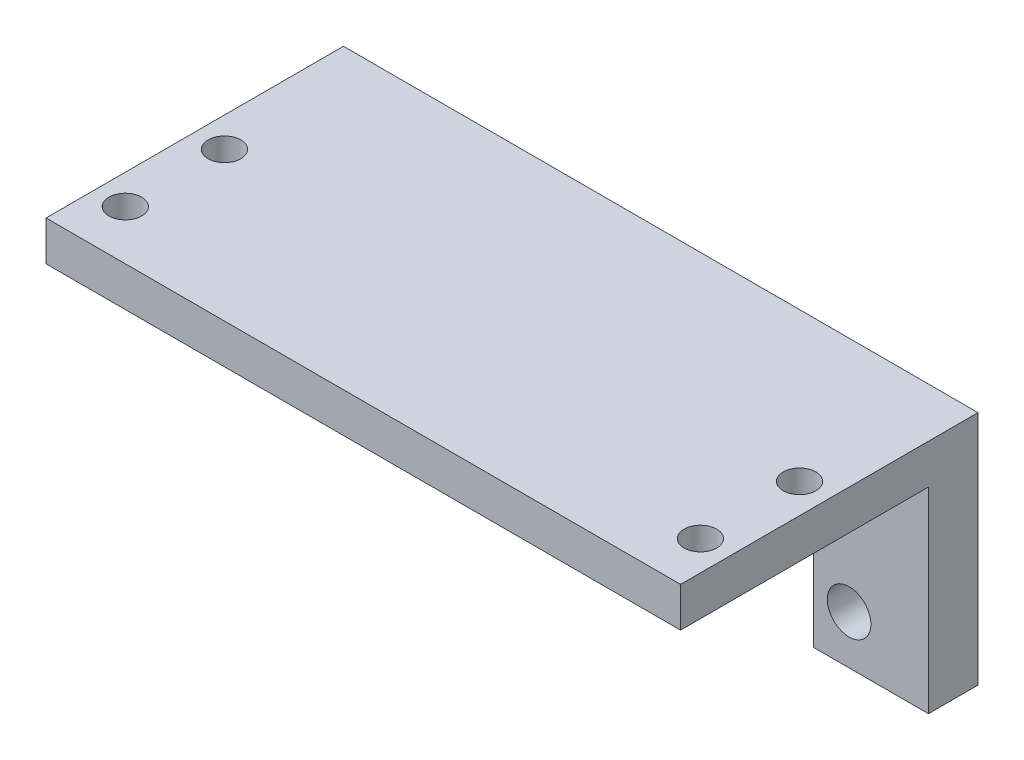
SolidWorks part; units mm, degrees
ref_plane "前视基准面" through (0, 0, 0) normal (0, 0, 1) x (1, 0, 0)
ref_plane "上视基准面" through (0, 0, 0) normal (0, 1, 0) x (1, 0, 0)
ref_plane "右视基准面" through (0, 0, 0) normal (1, 0, 0) x (0, 0, -1)
sketch "草图1" plane through (0, 0, 0) normal (0, 0, 1) x (1, 0, 0)
  line L0 (20.4, 0) -> (32, 0)
  line L1 (32, 0) -> (32, -19.8)
  line L2 (32, -19.8) -> (20.4, -19.8)
  line L3 (20.4, -19.8) -> (20.4, 0)
  line L4 (20.4, -9.9) -> (24.2798, -9.9) construction
  line L7 (0, 0) -> (0, -5.9432) construction
  line L12 (-32, -19.8) -> (-20.4, -19.8)
  line L13 (-32, 0) -> (-32, -19.8)
  line L14 (-20.4, 0) -> (-32, 0)
  line L15 (-20.4, -19.8) -> (-20.4, 0)
  circle A6 centre (24, -4.9) radius 2.2
  circle A7 centre (24, -14.9) radius 2.2
  circle A16 centre (-24, -14.9) radius 2.2
  circle A17 centre (-24, -4.9) radius 2.2
  point P4 (24, -4.9)
  point P14 (24, -14.9)
  point P21 (24, -4.9)
  point P22 (24, -14.9)
  dimension "D1" = 11.6
  dimension "D2" = 19.8
extrude "凸台-拉伸1" add sketch "草图1" along normal blind 5
sketch "草图3" plane through (0, 0, 0) normal (0, 1, 0) x (1, 0, 0)
  line L0 (32, 0) -> (32, -30)
  line L1 (32, -30) -> (-32, -30)
  line L2 (-32, -30) -> (-32, 0)
  line L3 (-32, 0) -> (32, 0)
  line L4 (0, 0) -> (0, -7.6096) construction
  circle A0 centre (-29, -15) radius 1.65
  circle A1 centre (-29, -25) radius 1.65
  circle A2 centre (29, -25) radius 1.65
  circle A3 centre (29, -15) radius 1.65
  dimension "D1" = 15
  dimension "D2" = 10
  dimension "D3" = 58
extrude "凸台-拉伸2" add sketch "草图3" along normal blind 4
